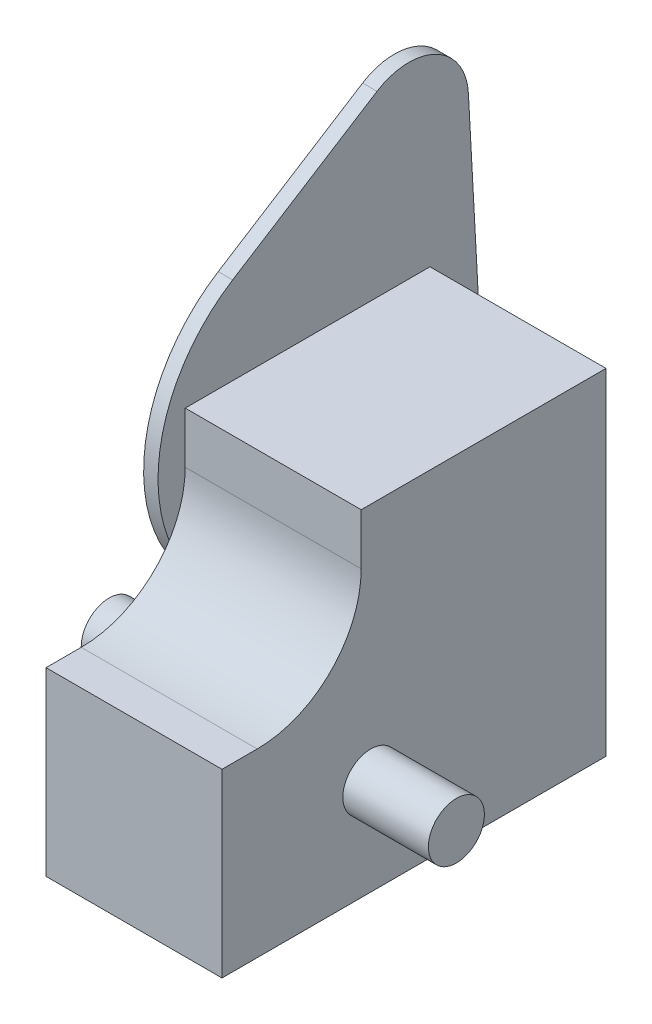
SolidWorks part; units mm, degrees
ref_plane "Front Plane" through (0, 0, 0) normal (0, 0, 1) x (1, 0, 0)
ref_plane "Top Plane" through (0, 0, 0) normal (0, 1, 0) x (1, 0, 0)
ref_plane "Right Plane" through (0, 0, 0) normal (1, 0, 0) x (0, 0, -1)
sketch "Sketch1" plane through (0, 0, 0) normal (1, 0, 0) x (0, 0, -1)
  line L0 (-130.0674, -21.123) -> (-69.1074, -21.123)
  line L1 (-69.1074, -21.123) -> (-69.1074, 32.217)
  line L2 (-69.1074, 32.217) -> (-107.9694, 32.217)
  line L3 (-130.0674, -21.123) -> (-130.0674, 7.579)
  line L4 (-130.0674, 7.579) -> (-124.4794, 7.579)
  line L5 (-107.9694, 32.217) -> (-107.9694, 24.089)
  arc A0 (-124.4794, 7.579) -> (-107.9694, 24.089) centre (-124.4794, 24.089) ccw
  dimension "D5" = 16.51
  dimension "D1" = 60.96
  dimension "D2" = 53.34
  dimension "D3" = 38.862
  dimension "D4" = 28.702
extrude "Extrude1" add sketch "Sketch1" along normal mid plane 27.94
sketch "Sketch2" plane through (0, 0, 0) normal (1, 0, 0) x (0, 0, -1)
  line L1 (-130.0674, -5.883) -> (-106.4454, -5.883) construction
  line L2 (-130.0674, 7.579) -> (-130.0674, -21.123) construction
  line L3 (-106.4454, -5.883) -> (-106.4454, -21.123) construction
  line L4 (-130.0674, -21.123) -> (-69.1074, -21.123) construction
  circle A0 centre (-106.4454, -5.883) radius 4.445
  dimension "D1" = 8.89
  dimension "D2" = 23.622
  dimension "D3" = 15.24
extrude "Extrude2" add sketch "Sketch2" along normal mid plane 55.118 separate body
sketch "Sketch3" plane through (-13.97, 0, 0) normal (-1, 0, 0) x (0, 0, 1)
  line L0 (69.1074, 32.217) -> (107.9694, 32.217) construction
  line L1 (69.1074, -21.123) -> (69.1074, 32.217) construction
  line L2 (63.0106, 53.0558) -> (61.5255, 25.9886)
  line L3 (77.5199, 60.545) -> (100.444, 46.0767)
  arc A0 (61.5255, 25.9886) -> (100.444, 46.0767) centre (86.8874, 24.597) ccw
  arc A1 (77.5199, 60.545) -> (63.0106, 53.0558) centre (72.4659, 52.537) ccw
  dimension "D1" = 50.8
  dimension "D3" = 17.78
  dimension "D4" = 27.94
  dimension "D2" = 7.62
extrude "Extrude3" add sketch "Sketch3" along normal blind 2.286 separate body
